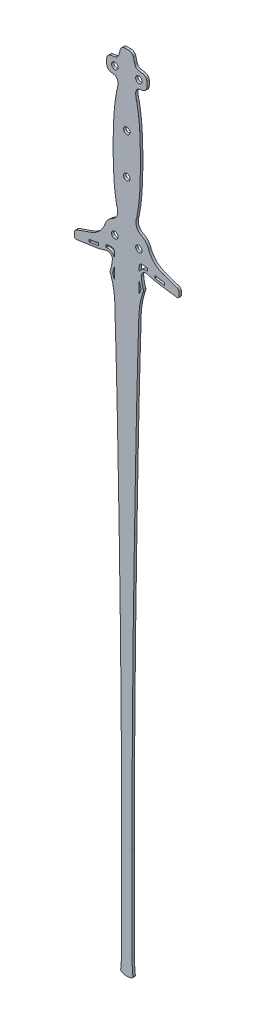
SolidWorks part; units mm, degrees
ref_plane "前视基准面" through (0, 0, 0) normal (0, 0, 1) x (1, 0, 0)
ref_plane "上视基准面" through (0, 0, 0) normal (0, 1, 0) x (1, 0, 0)
ref_plane "右视基准面" through (0, 0, 0) normal (1, 0, 0) x (0, 0, -1)
sketch "草图1" plane through (0, 0, 0) normal (0, 0, 1) x (1, 0, 0)
  line L0 (0, 0) -> (0, -16.254) construction
  line L19 (-20.0571, 213.3789) -> (-14.7569, 214.3276)
  line L20 (-10.0166, 218.6877) -> (-8.1877, 225.546)
  line L21 (10.0166, 218.6877) -> (8.1877, 225.546)
  line L22 (20.0571, 213.3789) -> (14.7569, 214.3276)
  line L27 (-2.3903, 230) -> (2.3903, 230)
  line L28 (-6.5, -745) -> (-6.5, -630)
  line L29 (6.5, -745) -> (6.5, -630)
  line L30 (-9.5599, -290) -> (-11, -210)
  line L31 (9.5599, -290) -> (11, -210)
  line L32 (-2.1314, 117) -> (-79.7073, 117) construction
  line L33 (-40, -3.4468) -> (-62.7186, -6.6757)
  line L34 (40, -3.4468) -> (62.7186, -6.6757)
  line L35 (45, 10) -> (62.3214, 3.9375)
  line L36 (-45, 10) -> (-62.3214, 3.9375)
  line L37 (65, -4.6956) -> (65, 0.1621)
  line L38 (-65, -4.6956) -> (-65, 0.1621)
  line L41 (-40, 2.5532) -> (-48.6933, 1.2042)
  line L42 (40, 2.5532) -> (48.6933, 1.2042)
  line L43 (-51, 3.1805) -> (-51, 7.9)
  line L44 (51, 3.1805) -> (51, 7.9)
  line L45 (-16.103, 194.7235) -> (-20.0419, 195.418)
  line L46 (-25, 201.3268) -> (-25, 207.4727)
  line L47 (25, 201.3268) -> (25, 207.4727)
  line L48 (16.103, 194.7235) -> (20.0419, 195.418)
  line L49 (-15.5, -27.1284) -> (-15.5, -10.865)
  line L50 (15.5, -27.1284) -> (15.5, -10.865)
  line L51 (-15.5, -2.6666) -> (-15.5, 6.7292)
  line L52 (-26, 3.1194) -> (-26, 6.2929)
  line L53 (-35, 0.5162) -> (-35, 3.5277)
  line L54 (-40, -0.4153) -> (-47, -1.4543)
  line L55 (-47, -1.4543) -> (-47, 1.467)
  line L56 (15.5, -2.6666) -> (15.5, 6.7292)
  line L57 (26, 3.1194) -> (26, 6.2929)
  line L58 (35, 0.5162) -> (35, 3.5277)
  line L59 (47, -1.4543) -> (47, 1.467)
  line L60 (40, -0.4153) -> (47, -1.4543)
  arc A0 (-18, -6) -> (-20.5173, -18.6749) centre (-64.8105, -3.2906) cw
  arc A1 (-20.4999, -21.3488) -> (-15, -50) centre (-107.8579, -52.9716) cw
  arc A3 (-26, 0) -> (-18, -6) centre (-23.99, -5.6533) cw
  arc A4 (-26, 0) -> (-40, -3.4468) centre (-50.1396, 67.8939) cw
  arc A5 (-45, 10) -> (-27, 28) centre (-54.6923, 37.6923) ccw
  arc A7 (-11.4778, 51.1255) -> (-12.5, 55) centre (-36.0839, 46.7055) ccw
  arc A10 (11.4778, 51.1255) -> (12.5, 55) centre (36.0839, 46.7055) cw
  arc A12 (45, 10) -> (27, 28) centre (54.6923, 37.6923) cw
  arc A13 (26, 0) -> (40, -3.4468) centre (50.1396, 67.8939) ccw
  arc A14 (26, 0) -> (18, -6) centre (23.99, -5.6533) ccw
  arc A16 (20.4999, -21.3488) -> (15, -50) centre (107.8579, -52.9716) ccw
  arc A17 (18, -6) -> (20.5173, -18.6749) centre (64.8105, -3.2906) ccw
  arc A20 (-6.5, -745) -> (-7.6, -766.499) centre (-217.1438, -745) cw
  arc A21 (-7.6, -766.499) -> (-6, -769) centre (-5.226, -766.7426) ccw
  arc A22 (-6, -769) -> (0, -770) centre (0, -751.5) ccw
  arc A23 (6, -769) -> (0, -770) centre (0, -751.5) cw
  arc A24 (7.6, -766.499) -> (6, -769) centre (5.226, -766.7426) cw
  arc A25 (6.5, -745) -> (7.6, -766.499) centre (217.1438, -745) ccw
  arc A26 (-6.5, -630) -> (-9.5599, -290) centre (-18897.4085, -630) ccw
  arc A27 (6.5, -630) -> (9.5599, -290) centre (18897.4085, -630) cw
  arc A28 (-11, -210) -> (-15, -50) centre (-11448.3342, -415.8834) ccw
  arc A29 (11, -210) -> (15, -50) centre (11448.3342, -415.8834) cw
  arc A30 (12.5, 179) -> (16.1638, 149) centre (-201.8664, 137.5968) cw
  arc A31 (16.1638, 149) -> (16.1638, 85) centre (-595.6772, 117) cw
  arc A32 (16.1638, 85) -> (12.5, 55) centre (-201.8664, 96.4032) cw
  arc A33 (-16.1638, 85) -> (-12.5, 55) centre (201.8664, 96.4032) ccw
  arc A34 (-16.1638, 149) -> (-16.1638, 85) centre (595.6772, 117) ccw
  arc A35 (-12.5, 179) -> (-16.1638, 149) centre (201.8664, 137.5968) ccw
  arc A36 (27, 28) -> (17.9693, 38.2474) centre (9.9901, 22.1126) ccw
  arc A37 (-27, 28) -> (-17.9693, 38.2474) centre (-9.9901, 22.1126) cw
  arc A38 (-11.1641, 189.2947) -> (-12.5, 179) centre (-36.0839, 187.2945) cw
  arc A39 (11.1641, 189.2947) -> (12.5, 179) centre (36.0839, 187.2945) ccw
  arc A40 (40, 2.5532) -> (27.0386, 5.9378) centre (50.1396, 67.8939) cw
  arc A41 (18.2343, 7.1154) -> (1.3852, -0.5719) centre (20.7781, -20.7688) ccw
  arc A42 (-18.2343, 7.1154) -> (-1.3852, -0.5719) centre (-20.7781, -20.7688) cw
  arc A43 (-40, 2.5532) -> (-27.0386, 5.9378) centre (-50.1396, 67.8939) ccw
  arc A44 (10.0166, 218.6877) -> (14.7569, 214.3276) centre (15.814, 220.2337) ccw
  arc A45 (-10.0166, 218.6877) -> (-14.7569, 214.3276) centre (-15.814, 220.2337) cw
  arc A46 (25, 201.3268) -> (20.0419, 195.418) centre (19, 201.3268) cw
  arc A47 (25, 207.4727) -> (20.0571, 213.3789) centre (19, 207.4727) ccw
  arc A48 (-20.0571, 213.3789) -> (-25, 207.4727) centre (-19, 207.4727) ccw
  arc A49 (-25, 201.3268) -> (-20.0419, 195.418) centre (-19, 201.3268) ccw
  arc A50 (20.5173, -18.6749) -> (20.4999, -21.3488) centre (16.7387, -19.9873) cw
  arc A51 (-20.5173, -18.6749) -> (-20.4999, -21.3488) centre (-16.7387, -19.9873) ccw
  arc A52 (62.3214, 3.9375) -> (65, 0.1621) centre (61, 0.1621) cw
  arc A53 (-62.3214, 3.9375) -> (-65, 0.1621) centre (-61, 0.1621) ccw
  arc A60 (1.3852, -0.5719) -> (-1.3852, -0.5719) centre (0, 0.8707) cw
  arc A61 (-62.7186, -6.6757) -> (-65, -4.6956) centre (-63, -4.6956) cw
  arc A62 (65, -4.6956) -> (62.7186, -6.6757) centre (63, -4.6956) cw
  arc A63 (51, 3.1805) -> (48.6933, 1.2042) centre (49, 3.1805) cw
  arc A64 (-48.6933, 1.2042) -> (-51, 3.1805) centre (-49, 3.1805) cw
  arc A65 (27.0386, 5.9378) -> (18.2343, 7.1154) centre (20.0513, -12.8019) ccw
  arc A66 (-18.2343, 7.1154) -> (-27.0386, 5.9378) centre (-20.0513, -12.8019) ccw
  arc A67 (11.4778, 51.1255) -> (17.9693, 38.2474) centre (23.2887, 49.0039) ccw
  arc A68 (-17.9693, 38.2474) -> (-11.4778, 51.1255) centre (-23.2887, 49.0039) ccw
  arc A69 (2.3903, 230) -> (8.1877, 225.546) centre (2.3903, 224) cw
  arc A70 (-2.3903, 230) -> (-8.1877, 225.546) centre (-2.3903, 224) ccw
  arc A71 (16.103, 194.7235) -> (11.1641, 189.2947) centre (17.1448, 188.8146) ccw
  arc A72 (-16.103, 194.7235) -> (-11.1641, 189.2947) centre (-17.1448, 188.8146) cw
  arc A73 (-17.8008, -19.9933) -> (-15.5, -10.865) centre (-64.8105, -3.2906) ccw
  arc A74 (-17.8008, -19.9933) -> (-15.5, -27.1284) centre (-107.8579, -52.9716) cw
  arc A75 (17.8008, -19.9933) -> (15.5, -27.1284) centre (107.8579, -52.9716) ccw
  arc A76 (17.8008, -19.9933) -> (15.5, -10.865) centre (64.8105, -3.2906) cw
  arc A77 (-26, 3.1194) -> (-15.5, -2.6666) centre (-23.99, -5.6533) cw
  arc A78 (-35, 0.5162) -> (-40, -0.4153) centre (-50.1396, 67.8939) cw
  arc A79 (26, 3.1194) -> (15.5, -2.6666) centre (23.99, -5.6533) ccw
  arc A80 (35, 0.5162) -> (40, -0.4153) centre (50.1396, 67.8939) ccw
  circle A82 centre (0, 142) radius 4.005
  circle A83 centre (0, 92) radius 4.005
  circle A85 centre (-15, 204.5) radius 4.005
  circle A86 centre (15, 204.5) radius 4.005
  circle A87 centre (-15, 22) radius 4.005
  circle A88 centre (15, 22) radius 4.005
  point P93 (17, 117)
  point P101 (-17, 117)
  point P104 (11, 215)
  point P108 (-11, 215)
  point P111 (25, 196.2923)
  point P114 (25, 212.4941)
  point P118 (-25, 212.4941)
  point P121 (-25, 196.2923)
  point P124 (21, -20)
  point P127 (-21, -20)
  point P130 (65, 3)
  point P133 (-65, 3)
  point P136 (12, 40)
  point P139 (-12, 40)
  point P142 (7, 230)
  point P145 (-7, 230)
  point P148 (12, 194)
  point P151 (-12, 194)
  point P154 (0, -2)
  point P157 (-65, -7)
  point P160 (65, -7)
  point P163 (51, 0.8462)
  point P166 (-51, 0.8462)
  point P169 (24.3686, 7)
  point P172 (-24.3686, 7)
  dimension "D35" = 10
  dimension "D37" = 6
  dimension "D38" = 33
  dimension "D23" = 130
  dimension "D27" = 6
  dimension "D29" = 34
  dimension "D18" = 25
  dimension "D34" = 18
  dimension "D39" = 9
  dimension "D40" = 28
  dimension "D48" = 6
  dimension "D49" = 4
  dimension "D50" = 2
  dimension "D51" = 20
  dimension "D52" = 12
  dimension "D53" = 6
  dimension "D55" = 3
  dimension "D56" = 3
  dimension "D57" = 3
  dimension "D59" = 3
  dimension "D61" = 8.01
  dimension "D64" = 8.01
  dimension "D65" = 8.01
  dimension "D66" = 15
  dimension "D70" = 8.01
  dimension "D1" = 40
  dimension "D2" = 1000
  dimension "D3" = 230
  dimension "D4" = 42
  dimension "D5" = 25
  dimension "D6" = 13
  dimension "D7" = 140
  dimension "D8" = 12
  dimension "D9" = 22
  dimension "D10" = 340
  dimension "D11" = 80
  dimension "D12" = 30
  dimension "D13" = 30
  dimension "D14" = 1
  dimension "D15" = 15.2
  dimension "D16" = 20
  dimension "D17" = 36
  dimension "D19" = 54
  dimension "D20" = 15
  dimension "D21" = 24
  dimension "D22" = 25
  dimension "D24" = 36
  dimension "D25" = 14
  dimension "D26" = 52
  dimension "D28" = 37
  dimension "D30" = 12
  dimension "D31" = 80
  dimension "D32" = 90
  dimension "D33" = 30
  dimension "D36" = 30
  dimension "D41" = 14
  dimension "D42" = 14
  dimension "D43" = 22
  dimension "D44" = 15
  dimension "D45" = 50
  dimension "D46" = 100
  dimension "D47" = 100.148
  dimension "D54" = 15.5
  dimension "D58" = 9
  dimension "D60" = 4
  dimension "D62" = 25
  dimension "D63" = 87.5
  dimension "D67" = 25
  dimension "D68" = 95
  dimension "D69" = 15
extrude "凸台-拉伸1" add sketch "草图1" along normal mid plane 3
fillet "圆角1" radius 0.2 18 edges at (-26, 6.2929, 0) (-26, 3.1194, 0) (-15.5, -2.6666, 0) (26, 6.2929, 0) (26, 3.1194, 0) (15.5, -2.6666, 0) (-15.5, -10.865, 0) (15.5, -10.865, 0) (15.5, -27.1284, 0) (-15.5, -27.1284, 0) (-35, 3.5277, 0) (-47, 1.467, 0) (35, 3.5277, 0) (47, 1.467, 0) (47, -1.4543, 0) (35, 0.5162, 0) (-35, 0.5162, 0) (-47, -1.4543, 0)
fillet "圆角2" radius 3 4 edges at (15.5, 6.7292, 0) (-15.5, 6.7292, 0) (17.8008, -19.9933, 0) (-17.8008, -19.9933, 0)
